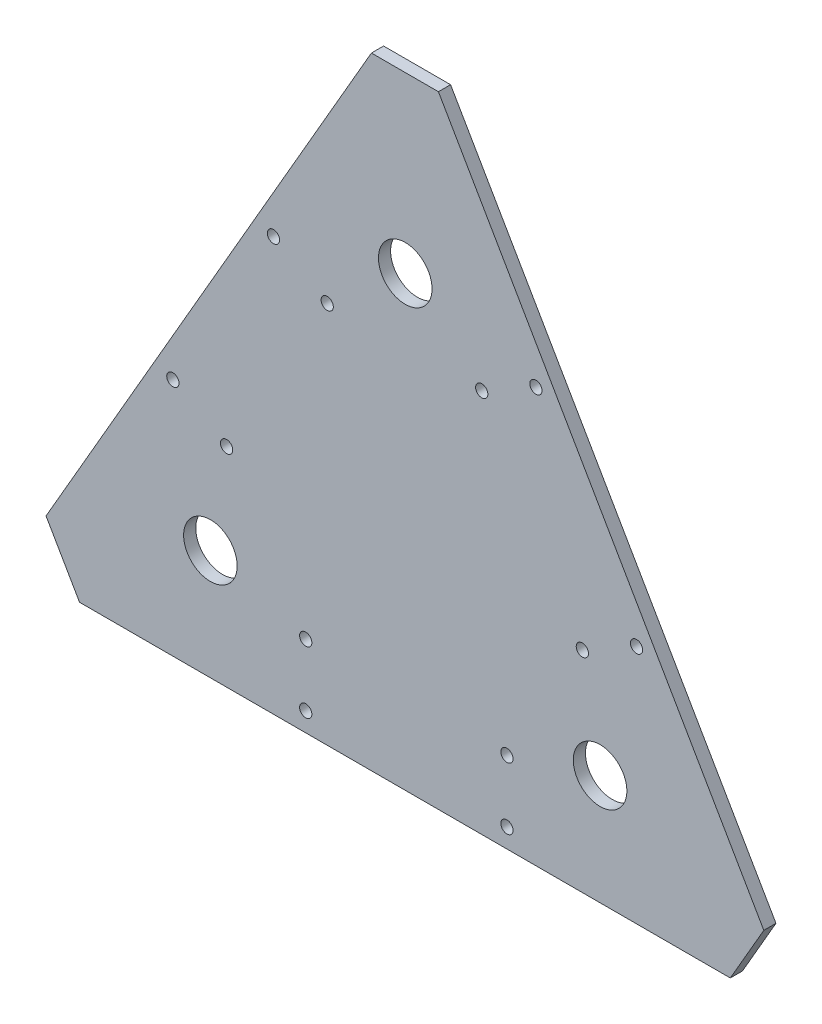
SolidWorks part; units mm, degrees
ref_plane "Front Plane" through (0, 0, 0) normal (0, 0, 1) x (1, 0, 0)
ref_plane "Top Plane" through (0, 0, 0) normal (0, 1, 0) x (1, 0, 0)
ref_plane "Right Plane" through (0, 0, 0) normal (1, 0, 0) x (0, 0, -1)
sketch "Sketch1" plane through (0, 0, 0) normal (0, 0, 1) x (1, 0, 0)
  line L0 (-647.4603, -317.6195) -> (-477.476, -23.1982)
  line L1 (-477.476, -23.1982) -> (-442.476, -23.1982)
  line L2 (-442.476, -23.1982) -> (-272.4917, -317.6195)
  line L3 (-272.4917, -317.6195) -> (-289.9917, -347.9304)
  line L4 (-289.9917, -347.9304) -> (-629.9603, -347.9304)
  line L5 (-629.9603, -347.9304) -> (-647.4603, -317.6195)
  line L16 (-459.8079, -231.5859) -> (-459.8079, -114.0541) construction
  circle A1 centre (-581.2092, -222.8693) radius 3.2
  circle A2 centre (-528.6492, -131.8327) radius 3.2
  circle A3 centre (-500.5777, -148.0115) radius 3.2
  circle A4 centre (-553.1368, -239.0465) radius 3.2
  circle A13 centre (-367.2942, -238.2091) radius 3.2
  circle A14 centre (-419.8542, -147.1725) radius 3.2
  circle A15 centre (-391.5457, -131.4121) radius 3.2
  circle A16 centre (-338.9857, -222.4487) radius 3.2
  circle A17 centre (-511.8008, -305.5304) radius 3.2
  circle A18 centre (-406.6805, -305.5304) radius 3.2
  circle A19 centre (-406.6806, -337.9304) radius 3.2
  circle A20 centre (-511.8006, -337.9304) radius 3.2
  circle A27 centre (-459.8079, -114.0541) radius 14
  circle A28 centre (-358.0223, -290.3519) radius 14
  circle A29 centre (-561.5935, -290.3519) radius 14
  point P6 (-526.8577, -193.5298)
  point P17 (-393.5776, -192.6927)
  point P20 (-459.8079, -217.9304)
  point P29 (-459.2405, -305.5304)
  point P61 (-511.8734, -202.181)
  dimension "D5" = 32.4
  dimension "D6" = 52.56
  dimension "D16" = 10
  dimension "D28" = 6.4
  dimension "D30" = 6.4
  dimension "D4" = 105.1182
  dimension "D7" = 105.12
  dimension "D8" = 32.4
  dimension "D9" = 10
  dimension "D10" = 42.4
  dimension "D11" = 52.56
  dimension "D12" = 110
  dimension "D13" = 10
  dimension "D14" = 105.12
  dimension "D15" = 110
  dimension "D17" = 32.4
  dimension "D18" = 130
  dimension "D19" = 105.12
  dimension "D20" = 10
  dimension "D21" = 42.4
  dimension "D22" = 10
  dimension "D23" = 10
  dimension "D24" = 339.9685
  dimension "D25" = 32.4
  dimension "D27" = 52.56
  dimension "D29" = 105.12
  dimension "D31" = 42.4
  dimension "D36" = 3
extrude "Boss-Extrude1" add sketch "Sketch1" against normal blind 6.35
sketch "Sketch4" plane through (0, 0, 0) normal (0, 0, 1) x (1, 0, 0)
  line L0 (-349.7763, -150.6062) -> (-449.7763, -323.8113)
  line L1 (-449.7763, -323.8113) -> (-469.7763, -323.8113)
  line L2 (-469.7763, -323.8113) -> (-569.7763, -150.6062)
  line L8 (-569.7763, -150.6062) -> (-569.7763, -23.2857)
  line L9 (-569.7763, -23.2857) -> (-349.7763, -23.2857)
  line L10 (-349.7763, -150.6062) -> (-349.7763, -23.2857)
  line L11 (-289.9917, -347.9304) -> (-629.9603, -347.9304) construction
  circle A0 centre (-407.8463, -172.5859) radius 11
  circle A1 centre (-459.8079, -202.5859) radius 24
  circle A2 centre (-511.7694, -172.5859) radius 11
  circle A3 centre (-459.8079, -262.5859) radius 11
  point P6 (-459.8079, -202.5859)
  point P19 (-459.8079, -202.5859)
  point P21 (-459.8079, -182.9304)
  dimension "D5" = 60
  dimension "D6" = 48
  dimension "D3" = 22
  dimension "D7" = 3
  dimension "D1" = 200
  dimension "D2" = 60
  dimension "D4" = 60
  dimension "D11" = 165
sketch "Sketch5" plane through (0, 0, 0) normal (0, 0, 1) x (1, 0, 0)
  line L0 (-349.7763, -150.6062) -> (-449.7763, -323.8113)
  line L1 (-449.7763, -323.8113) -> (-469.7763, -323.8113)
  line L2 (-469.7763, -323.8113) -> (-569.7763, -150.6062)
  line L6 (-289.9917, -347.9304) -> (-629.9603, -347.9304) construction
  line L8 (-569.7763, -150.6062) -> (-569.7763, -23.2857)
  line L9 (-569.7763, -23.2857) -> (-349.7763, -23.2857)
  line L10 (-349.7763, -150.6062) -> (-349.7763, -23.2857)
  circle A0 centre (-407.8463, -172.5859) radius 11.375
  circle A1 centre (-459.8079, -202.5859) radius 24
  circle A5 centre (-407.8463, -172.5859) radius 22
  circle A6 centre (-407.8463, -172.5859) radius 14.625 construction
  circle A7 centre (-406.2939, -191.0207) radius 1.75
  circle A8 centre (-426.2811, -174.1384) radius 1.75
  circle A9 centre (-409.3988, -154.1512) radius 1.75
  circle A10 centre (-389.4116, -171.0335) radius 1.75
  circle A11 centre (-459.8079, -262.5859) radius 11.375
  circle A12 centre (-459.8079, -262.5859) radius 22
  circle A13 centre (-476.549, -254.713) radius 1.75
  circle A14 centre (-451.9349, -245.8448) radius 1.75
  circle A15 centre (-443.0667, -270.4589) radius 1.75
  circle A16 centre (-467.6808, -279.3271) radius 1.75
  circle A17 centre (-459.8079, -262.5859) radius 14.625 construction
  circle A18 centre (-511.7694, -172.5859) radius 11.375
  circle A19 centre (-511.7694, -172.5859) radius 22
  circle A20 centre (-496.5806, -162.0241) radius 1.75
  circle A21 centre (-501.2076, -187.7747) radius 1.75
  circle A22 centre (-526.9581, -183.1478) radius 1.75
  circle A23 centre (-522.3312, -157.3972) radius 1.75
  circle A24 centre (-511.7694, -172.5859) radius 14.625 construction
  circle A25 centre (-511.7694, -172.5859) radius 14.625
  circle A26 centre (-407.8463, -172.5859) radius 14.625
  circle A27 centre (-459.8079, -262.5859) radius 14.625
  point P6 (-459.8079, -202.5859)
  point P19 (-459.8079, -202.5859)
  point P21 (-459.8079, -182.9304)
  point P27 (-407.8463, -172.5859)
  point P41 (-459.8079, -262.5859)
  point P55 (-511.7694, -172.5859)
  point P56 (-459.8079, -202.5859)
  dimension "D5" = 60
  dimension "D6" = 48
  dimension "D3" = 22.75
  dimension "D7" = 3.5
  dimension "D2" = 44
  dimension "D4" = 3.25
  dimension "D8" = 18.5
  dimension "D12" = 85.3445
  dimension "D1" = 200
  dimension "D9" = 4
  dimension "D10" = 3
  dimension "D11" = 239.3003
